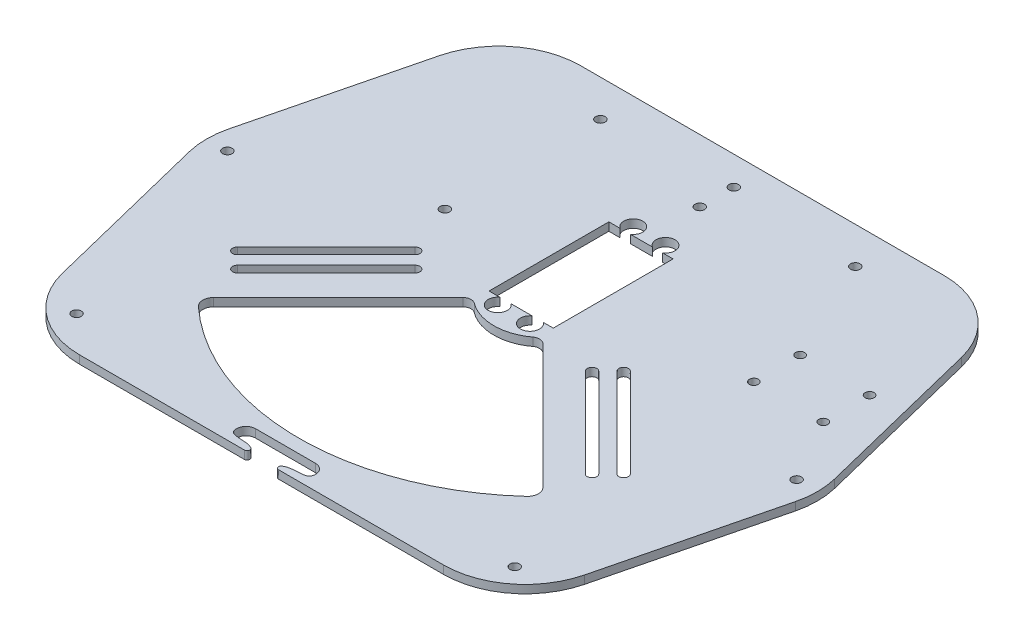
SolidWorks part; units mm, degrees
ref_plane "前视基准面" through (0, 0, 0) normal (0, 0, 1) x (1, 0, 0)
ref_plane "上视基准面" through (0, 0, 0) normal (0, 1, 0) x (1, 0, 0)
ref_plane "右视基准面" through (0, 0, 0) normal (1, 0, 0) x (0, 0, -1)
sketch "草图1" plane through (0, 0, 0) normal (0, 1, 0) x (1, 0, 0)
  line L3 (-66.7806, 154.594) -> (66.7806, 154.594)
  line L4 (-95.8987, 131.8145) -> (-111.2655, 69.8447)
  line L5 (-96.25, 148.3486) -> (-96.25, 83.3486) construction
  line L6 (95.8987, 131.8145) -> (111.2655, 69.8447)
  line L7 (95.8987, -6.5662) -> (111.2655, 55.4037)
  line L9 (-95.8987, -6.5662) -> (-111.2655, 55.4037)
  line L10 (137.9048, 62.6242) -> (-113.2043, 62.6242) construction
  line L12 (-66.7806, -29.3457) -> (66.7806, -29.3457)
  line L20 (0, 9.3997) -> (0, 129.3997) construction
  arc A0 (95.8987, -6.5662) -> (66.7806, -29.3457) centre (66.7806, 0.6543) cw
  arc A1 (-66.7806, -29.3457) -> (-95.8987, -6.5662) centre (-66.7806, 0.6543) cw
  arc A2 (111.2655, 55.4037) -> (111.2655, 69.8447) centre (82.1474, 62.6242) ccw
  arc A3 (-111.2655, 69.8447) -> (-111.2655, 55.4037) centre (-82.1474, 62.6242) ccw
  arc A6 (-66.7806, 154.594) -> (-95.8987, 131.8145) centre (-66.7806, 124.594) ccw
  arc A7 (95.8987, 131.8145) -> (66.7806, 154.594) centre (66.7806, 124.594) ccw
  point P16 (-90.25, 154.594)
  point P18 (90.25, -29.3457)
  point P24 (-90.25, -29.3457)
  point P26 (0, 62.6242)
  point P27 (90.25, 154.594)
  point P28 (113.2043, 62.6242)
  dimension "D5" = 30
  dimension "D6" = 30
extrude "凸台-拉伸1" add sketch "草图1" along normal blind 3
sketch "草图2" plane through (0, 3, 0) normal (0, 1, 0) x (1, 0, 0)
  line L0 (0, 0) -> (0, 144.0797) construction
  circle A0 centre (104.5075, 62.6242) radius 1.75 construction
  circle A1 centre (80.4502, -16.819) radius 1.75 construction
  circle A2 centre (-80.4502, -16.819) radius 1.75 construction
  circle A3 centre (-104.5075, 62.6242) radius 1.75 construction
  circle A4 centre (104.5075, 62.6242) radius 1.75
  circle A5 centre (80.4502, -16.819) radius 1.75
  circle A6 centre (-80.4502, -16.819) radius 1.75
  circle A7 centre (-104.5075, 62.6242) radius 1.75
  circle A8 centre (0, 144.0797) radius 1.75
  circle A9 centre (0, 131.5682) radius 1.75
  dimension "D1" = 3.5
  dimension "D2" = 3.5
extrude "切除-拉伸1" cut sketch "草图2" against normal blind 10
sketch "草图3" plane through (0, 3, 0) normal (0, 1, 0) x (1, 0, 0)
  line L0 (0, 73.9628) -> (0, -4.1514) construction
  line L1 (14.6969, 59.2658) -> (44.7749, 29.1878)
  line L2 (-14.6969, 59.2658) -> (-44.7749, 29.1878)
  arc A1 (-10.7791, 59.5471) -> (10.7791, 59.5471) centre (0, 73.9628) ccw
  arc A2 (-44.6722, 24.8472) -> (44.6722, 24.8472) centre (0, 73.9628) ccw
  arc A3 (-44.7749, 29.1878) -> (-44.6722, 24.8472) centre (-42.6536, 27.0665) ccw
  arc A4 (44.6722, 24.8472) -> (44.7749, 29.1878) centre (42.6536, 27.0665) ccw
  arc A5 (14.6969, 59.2658) -> (10.7791, 59.5471) centre (12.5756, 57.1445) ccw
  arc A6 (-10.7791, 59.5471) -> (-14.6969, 59.2658) centre (-12.5756, 57.1445) ccw
  point P9 (-46.9465, 27.0163)
  point P12 (46.9465, 27.0163)
  point P15 (12.7279, 61.2349)
  point P18 (-12.7279, 61.2349)
  point P19 (0, 0)
  dimension "D1" = 36
  dimension "D3" = 3
  dimension "D2" = 45
extrude "切除-拉伸2" cut sketch "草图3" against normal blind 10
sketch "草图4" plane through (0, 3, 0) normal (0, 1, 0) x (1, 0, 0)
  line L0 (-36.8579, 37.1049) -> (-60.4293, 13.5335)
  line L1 (-14.6969, 59.2658) -> (-44.7749, 29.1878) construction
  line L2 (36.8579, 37.1049) -> (60.4293, 13.5335)
  line L3 (44.7749, 29.1878) -> (14.6969, 59.2658) construction
  line L4 (-36.8579, 37.1049) -> (36.8579, 37.1049)
  arc A0 (-60.294, 7.7475) -> (60.294, 7.7475) centre (0, 73.9628) ccw
  arc A1 (60.4293, 13.5335) -> (60.294, 7.7475) centre (57.6009, 10.7051) cw
  arc A2 (-60.294, 7.7475) -> (-60.4293, 13.5335) centre (-57.6009, 10.7051) cw
  dimension "D1" = 4
extrude "切除-拉伸3" cut sketch "草图4" against normal blind 10
sketch "草图5" plane through (0, 3, 0) normal (0, 1, 0) x (1, 0, 0)
  circle A0 centre (47.5277, 141.1486) radius 1.75 construction
  circle A1 centre (47.5277, 141.1486) radius 1.75
  circle A2 centre (-46.0695, 84.051) radius 1.75 construction
  circle A3 centre (-46.0695, 141.1486) radius 1.75 construction
  circle A4 centre (-46.0695, 84.051) radius 1.75
  circle A5 centre (-46.0695, 141.1486) radius 1.75
extrude "切除-拉伸4" cut sketch "草图5" against normal blind 10
sketch "草图6" plane through (0, 3, 0) normal (0, 1, 0) x (1, 0, 0)
  circle A0 centre (65.5507, 102.8648) radius 1.65
  circle A1 centre (91.0507, 102.8648) radius 1.65
  circle A2 centre (91.0507, 85.8648) radius 1.65
  circle A4 centre (65.5507, 85.8648) radius 1.65
  dimension "D1" = 3.3
  dimension "D2" = 3.3
  dimension "D3" = 25.5
  dimension "D4" = 3.3
  dimension "D5" = 17
extrude "切除-拉伸5" cut sketch "草图6" against normal blind 10
sketch "草图7" plane through (0, 3, 0) normal (0, 1, 0) x (1, 0, 0)
  line L0 (0, 0) -> (0, -60.3268) construction
  line L1 (-11.0166, -24.0139) -> (11.0166, -24.0139) construction
  line L2 (-11.0166, -20.5139) -> (11.0166, -20.5139)
  line L3 (-6.2934, -29.3457) -> (-8.7556, -29.3457)
  line L4 (6.2934, -29.3457) -> (8.7556, -29.3457)
  line L5 (-66.7806, -29.3457) -> (66.7806, -29.3457) construction
  line L6 (8.7556, -29.3457) -> (8.7556, -31.4124)
  line L7 (8.7556, -31.4124) -> (-8.7556, -31.4124)
  line L8 (-8.7556, -31.4124) -> (-8.7556, -29.8045)
  line L9 (-8.7556, -29.8045) -> (-8.7556, -29.3457)
  arc A0 (-11.0166, -20.5139) -> (-14.3785, -24.9877) centre (-11.0166, -24.0139) ccw
  arc A1 (14.3785, -24.9877) -> (11.0166, -20.5139) centre (11.0166, -24.0139) ccw
  arc A2 (-6.2934, -29.3457) -> (-5.8046, -27.4733) centre (-6.2934, -28.3457) ccw
  arc A3 (6.2934, -29.3457) -> (5.8046, -27.4733) centre (6.2934, -28.3457) cw
  spline S0 degree 3 poles (-14.3785, -24.9877) (-14.0507, -26.1193) (-10.4893, -26.7601) (-7.7247, -26.4938) (-5.9045, -27.4173) (-5.8046, -27.4733) knots 0 0 0 0 0.274124 0.74549 0.777394 0.777394 0.777394 0.777394
  spline S1 degree 3 poles (14.3785, -24.9877) (14.0507, -26.1193) (10.4893, -26.7601) (7.7247, -26.4938) (5.9045, -27.4173) (5.8046, -27.4733) knots 0 0 0 0 0.274124 0.74549 0.777394 0.777394 0.777394 0.777394
  point P6 (0, -24.0139)
  dimension "D1" = 3.5
  dimension "D2" = 1
extrude "切除-拉伸8" cut sketch "草图7" against normal blind 10
sketch "草图8" plane through (0, 3, 0) normal (0, 1, 0) x (1, 0, 0)
  line L0 (-32.4682, 59.5397) -> (-65.1112, 26.8968) construction
  line L1 (-31.2308, 58.3023) -> (-63.8737, 25.6593)
  line L2 (-33.7057, 60.7771) -> (-66.3486, 28.1342)
  line L3 (0, 65.2452) -> (0, -11.8785) construction
  line L4 (-38.2643, 65.3357) -> (-70.9072, 32.6928) construction
  line L5 (-37.0268, 64.0983) -> (-69.6698, 31.4553)
  line L6 (-39.5017, 66.5732) -> (-72.1446, 33.9302)
  line L7 (38.2643, 65.3357) -> (70.9072, 32.6928) construction
  line L8 (37.0268, 64.0983) -> (69.6698, 31.4553)
  line L9 (39.5017, 66.5732) -> (72.1446, 33.9302)
  line L10 (32.4682, 59.5397) -> (65.1112, 26.8968) construction
  line L11 (31.2308, 58.3023) -> (63.8737, 25.6593)
  line L12 (33.7057, 60.7771) -> (66.3486, 28.1342)
  arc A0 (-31.2308, 58.3023) -> (-33.7057, 60.7771) centre (-32.4682, 59.5397) ccw
  arc A1 (-66.3486, 28.1342) -> (-63.8737, 25.6593) centre (-65.1112, 26.8968) ccw
  arc A2 (-37.0268, 64.0983) -> (-39.5017, 66.5732) centre (-38.2643, 65.3357) ccw
  arc A3 (-72.1446, 33.9302) -> (-69.6698, 31.4553) centre (-70.9072, 32.6928) ccw
  arc A4 (37.0268, 64.0983) -> (39.5017, 66.5732) centre (38.2643, 65.3357) cw
  arc A5 (72.1446, 33.9302) -> (69.6698, 31.4553) centre (70.9072, 32.6928) cw
  arc A6 (31.2308, 58.3023) -> (33.7057, 60.7771) centre (32.4682, 59.5397) cw
  arc A7 (66.3486, 28.1342) -> (63.8737, 25.6593) centre (65.1112, 26.8968) cw
  point P2 (-48.7897, 43.2182)
  point P12 (-54.5857, 49.0143)
  point P19 (54.5857, 49.0143)
  point P26 (48.7897, 43.2182)
  dimension "D1" = 1.75
extrude "切除-拉伸9" cut sketch "草图8" against normal blind 10
sketch "草图9" plane through (0, 3, 0) normal (0, 1, 0) x (1, 0, 0)
  line L0 (-3.845, 66.1263) -> (3.845, 66.1263)
  line L1 (-11.9309, 110.1191) -> (-7.8069, 110.1191)
  line L2 (-11.9309, 110.1191) -> (-11.9309, 66.1263)
  line L3 (-11.9309, 66.1263) -> (-7.9934, 66.1263)
  line L4 (11.6582, 110.1191) -> (11.6582, 66.1263)
  line L5 (7.9934, 66.1263) -> (11.6582, 66.1263)
  line L6 (7.8069, 110.1191) -> (11.6582, 110.1191)
  line L7 (-4.0315, 110.1191) -> (4.0315, 110.1191)
  arc A0 (7.8069, 110.1191) -> (4.0315, 110.1191) centre (5.9192, 113.0664) ccw
  arc A1 (-4.0315, 110.1191) -> (-7.8069, 110.1191) centre (-5.9192, 113.0664) ccw
  arc A2 (-7.9934, 66.1263) -> (-3.845, 66.1263) centre (-5.9192, 63.3071) ccw
  arc A3 (3.845, 66.1263) -> (7.9934, 66.1263) centre (5.9192, 63.3071) ccw
extrude "切除-拉伸10" cut sketch "草图9" against normal blind 10
